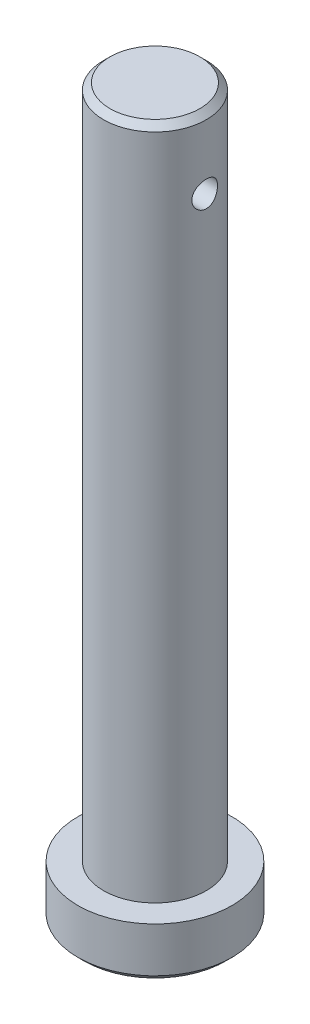
SolidWorks part; units mm, degrees
ref_plane "Front Plane" through (0, 0, 0) normal (0, 0, 1) x (1, 0, 0)
ref_plane "Top Plane" through (0, 0, 0) normal (0, 1, 0) x (1, 0, 0)
ref_plane "Right Plane" through (0, 0, 0) normal (1, 0, 0) x (0, 0, -1)
sketch "Sketch1" plane through (0, 0, 0) normal (0, 1, 0) x (1, 0, 0)
  circle A0 centre (0, 0) radius 12
  dimension "D1" = 24
extrude "Boss-Extrude1" add sketch "Sketch1" along normal blind 8
chamfer "Chamfer1" distance 1 angle 45 1 edges at (0, 0, 12)
sketch "Sketch2" plane through (0, 8, 0) normal (0, 1, 0) x (1, 0, 0)
  circle A0 centre (0, 0) radius 8
  dimension "D1" = 16
extrude "Boss-Extrude2" add sketch "Sketch2" along normal blind 105
chamfer "Chamfer2" distance 1 angle 45 1 edges at (0, 113, 8)
sketch "Sketch3" plane through (0, 0, 0) normal (1, 0, 0) x (0, 0, -1)
  line L0 (12, 8) -> (-12, 8) construction
  circle A0 centre (0, 102) radius 2
  dimension "D1" = 4
  dimension "D2" = 94
extrude "Cut-Extrude1" cut sketch "Sketch3" against normal mid plane 105
